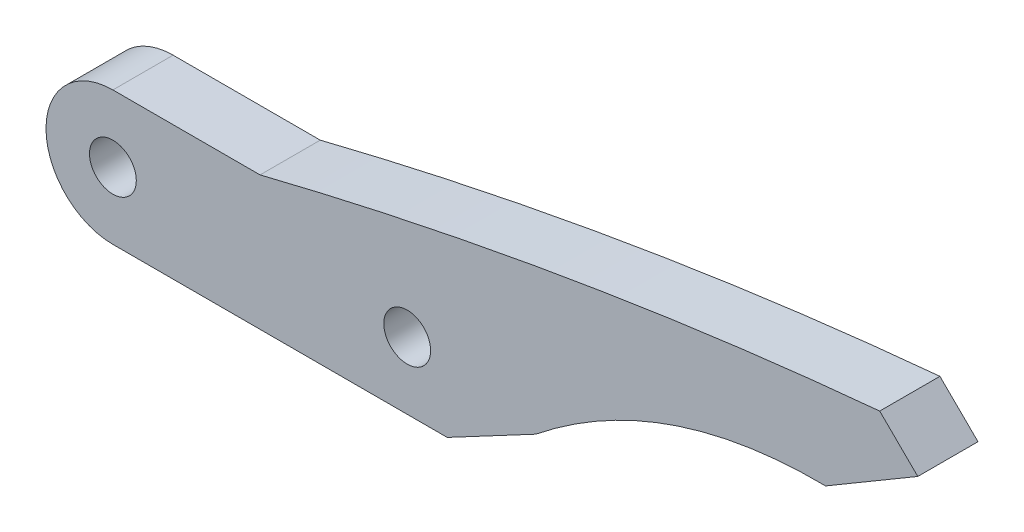
SolidWorks part; units mm, degrees
ref_plane "Front Plane" through (0, 0, 0) normal (0, 0, 1) x (1, 0, 0)
ref_plane "Top Plane" through (0, 0, 0) normal (0, 1, 0) x (1, 0, 0)
ref_plane "Right Plane" through (0, 0, 0) normal (1, 0, 0) x (0, 0, -1)
sketch "Sketch1" plane through (0, 0, 0) normal (0, 0, 1) x (1, 0, 0)
  line L0 (0, 6.942) -> (0, -7.5363) construction
  line L1 (-16, 5) -> (16, 5)
  line L2 (-16, 5) -> (-16, -5)
  line L3 (-16, -5) -> (16, -5)
  line L4 (16, 5) -> (16, -5)
  line L5 (-16, 5) -> (16, -5) construction
  line L6 (-16, -5) -> (16, 5) construction
  line L7 (-11, 0) -> (11, 0) construction
  circle A0 centre (-11, 0) radius 5
  circle A1 centre (11, 0) radius 5
  circle A2 centre (-11, 0) radius 1.75
  circle A3 centre (11, 0) radius 1.75
  point P0 (0, 0)
  dimension "D1" = 10
  dimension "D2" = 3.5
  dimension "D3" = 22
extrude "Boss-Extrude1" add sketch "Sketch1" along normal blind 4.5 contours L3 A1 L1 A0 | A0 A2 | A1 A3
sketch "Sketch2" plane through (0, 0, 4.5) normal (0, 0, 1) x (1, 0, 0)
  line L0 (46.3165, 12.87) -> (49.1632, 10.06)
  line L1 (49.1632, 10.06) -> (42.27, 6)
  line L2 (20.61, -1.48) -> (13.99, -5)
  line L3 (13.99, -5) -> (11, -5)
  line L4 (-11, -5) -> (11, -5) construction
  line L5 (-11, 5) -> (11, 5) construction
  line L6 (0, 5) -> (11, 5)
  arc A2 (11, -5) -> (11, 5) centre (11, 0) ccw construction
  arc A3 (11, -5) -> (11, 5) centre (11, 0) ccw
  spline S0 degree 2 poles (42.27, 6) (30.1462, 6.1573) (20.61, -1.48) knots 0 0 0 1 1 1
  spline S1 degree 2 poles (0, 5) (22.8629, 10.6997) (46.3165, 12.87) knots 0 0 0 1 1 1
  point P10 (11, 0)
  dimension "D1" = 4
  dimension "D2" = 8
  dimension "D3" = 15.06
  dimension "D4" = 17.87
  dimension "D5" = 11
  dimension "D6" = 9.45
  dimension "D7" = 20.52
  dimension "D8" = 31.27
  dimension "D9" = 3.52
  dimension "D10" = 9.61
  dimension "D11" = 2.99
  dimension "D12" = 13.52
  dimension "D13" = 15.07
extrude "Boss-Extrude2" add sketch "Sketch2" against normal up to surface (4.5 mm away) up to face at (0, 0, 0)
